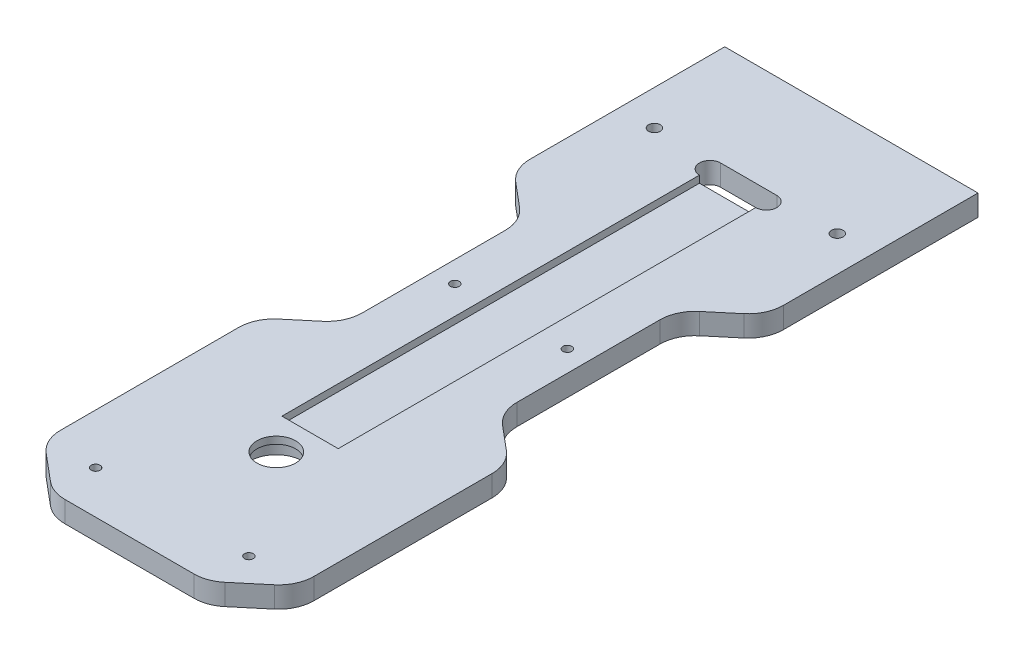
SolidWorks part; units mm, degrees
ref_plane "Front Plane" through (0, 0, 0) normal (0, 0, 1) x (1, 0, 0)
ref_plane "Top Plane" through (0, 0, 0) normal (0, 1, 0) x (1, 0, 0)
ref_plane "Right Plane" through (0, 0, 0) normal (1, 0, 0) x (0, 0, -1)
sketch "Sketch1" plane through (0, 0, 0) normal (0, 1, 0) x (1, 0, 0)
  line L0 (21.2131, -102.2276) -> (35.2131, -90.4802)
  line L1 (35.2131, -90.4802) -> (35.2131, -30.4802)
  line L2 (35.2131, -30.4802) -> (21.2131, -18.7328)
  line L3 (21.2131, -18.7328) -> (21.2131, 31.2672)
  line L4 (21.2131, 31.2672) -> (35.2131, 43.0146)
  line L5 (35.2131, 43.0146) -> (35.2131, 103.0146)
  line L6 (35.2131, 103.0146) -> (-36.7869, 103.0146)
  line L7 (-36.7869, 103.0146) -> (-36.7869, 43.0146)
  line L8 (-36.7869, 43.0146) -> (-22.7869, 31.2672)
  line L9 (-22.7869, 31.2672) -> (-22.7869, -18.7328)
  line L10 (-22.7869, -18.7328) -> (-36.7869, -30.4802)
  line L11 (-36.7869, -30.4802) -> (-36.7869, -90.4802)
  line L12 (-36.7869, -90.4802) -> (-22.7869, -102.2276)
  line L13 (-22.7869, -102.2276) -> (21.2131, -102.2276)
extrude "Boss-Extrude1" add sketch "Sketch1" along normal blind 6
fillet "Fillet1" radius 10 8 edges at (35.2131, 3, 30.4802) (21.2131, 3, 18.7328) (-22.7869, 3, 18.7328) (-36.7869, 3, 30.4802) (35.2131, 3, 90.4802) (21.2131, 3, 102.2276) (-22.7869, 3, 102.2276) (-36.7869, 3, 90.4802)
sketch "Sketch2" plane through (0, 0, 0) normal (0, -1, 0) x (1, 0, 0)
  line L1 (-36.7869, 60.4802) -> (21.737, 60.4802) construction
  line L2 (-36.7869, 35.1433) -> (-36.7869, 85.8172) construction
  circle A0 centre (-0.7869, 60.4802) radius 2.5
  dimension "D2" = 5
  dimension "D1" = 36
extrude "Cut-Extrude1" cut sketch "Sketch2" against normal blind 6
sketch "Sketch4" plane through (0, 0, 0) normal (0, -1, 0) x (1, 0, 0)
  line L0 (35.2131, -43.0146) -> (35.2131, -103.0146) construction
  line L1 (-36.7869, -103.0146) -> (35.2131, -103.0146)
  line L2 (-36.7869, -103.0146) -> (-36.7869, -99.0146)
  line L3 (-36.7869, -99.0146) -> (35.2131, -99.0146)
  line L4 (35.2131, -103.0146) -> (35.2131, -99.0146)
  dimension "D1" = 4
sketch "Sketch5" plane through (0, 0, 0) normal (0, -1, 0) x (1, 0, 0)
  circle A0 centre (-0.7869, 60.4802) radius 7.5
  dimension "D1" = 15
extrude "Cut-Extrude3" cut sketch "Sketch5" against normal blind 4
sketch "Sketch6" plane through (0, 4, 0) normal (0, -1, 0) x (1, 0, 0)
  circle A0 centre (-0.7869, 60.4802) radius 5.5
  dimension "D1" = 11
extrude "Cut-Extrude4" cut sketch "Sketch6" against normal blind 4
sketch "Sketch8" plane through (0, 6, 0) normal (0, 1, 0) x (1, 0, 0)
  line L0 (-8.7869, -50.8756) -> (7.2131, -50.8756)
  line L2 (-8.7869, -50.8756) -> (7.2131, -50.8756)
  line L3 (-8.7869, -50.8756) -> (-8.7869, 70.8241)
  line L4 (-8.7869, 70.8241) -> (7.2131, 70.8241)
  line L5 (7.2131, -50.8756) -> (7.2131, 70.8241)
  dimension "D2" = 16
  dimension "D3" = 16
extrude "Cut-Extrude5" cut sketch "Sketch8" against normal blind 2 contours L0 L5 L4 L3
fillet "Fillet2" radius 10 4 edges at (35.2131, 3, -43.0146) (21.2131, 3, -31.2672) (-22.7869, 3, -31.2672) (-36.7869, 3, -43.0146)
sketch "Sketch9" plane through (0, 6, 0) normal (0, 1, 0) x (1, 0, 0)
  line L0 (7.2131, 70.8241) -> (-8.7869, 70.8241) construction
  line L1 (7.2131, 67.8241) -> (-8.7869, 67.8241)
  line L2 (7.2131, 73.8241) -> (-8.7869, 73.8241)
  arc A0 (7.2131, 67.8241) -> (7.2131, 73.8241) centre (7.2131, 70.8241) ccw
  arc A1 (-8.7869, 73.8241) -> (-8.7869, 67.8241) centre (-8.7869, 70.8241) ccw
  point P4 (-0.7869, 70.8241)
  dimension "D1" = 6
extrude "Cut-Extrude6" cut sketch "Sketch9" against normal blind 10
sketch "Sketch10" plane through (0, 0, 0) normal (0, -1, 0) x (1, 0, 0)
  circle A0 centre (-16.7869, -6.2672) radius 1.25
  circle A1 centre (15.2131, -6.2672) radius 1.25
extrude "Cut-Extrude7" cut sketch "Sketch10" against normal blind 10
sketch "Sketch11" plane through (0, 6, 0) normal (0, 1, 0) x (1, 0, 0)
  circle A0 centre (20.9936, -90.0433) radius 1.25
  circle A1 centre (-22.5674, -90.0433) radius 1.25
  dimension "D1" = 2.5
  dimension "D2" = 2.5
extrude "Cut-Extrude8" cut sketch "Sketch11" against normal blind 10
sketch "Sketch12" plane through (0, 6, 0) normal (0, 1, 0) x (1, 0, 0)
  circle A0 centre (25.2131, 73.0146) radius 1.65
  circle A1 centre (-26.7869, 73.0146) radius 1.65
  dimension "D1" = 3.3
extrude "Cut-Extrude9" cut sketch "Sketch12" against normal blind 10
